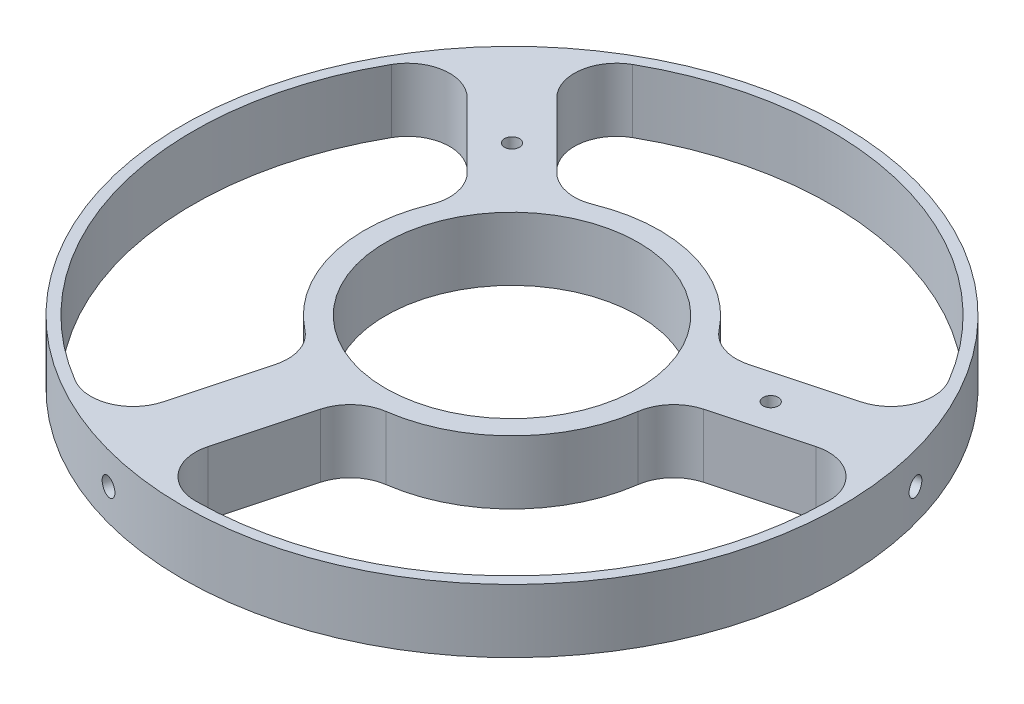
SolidWorks part; units mm, degrees
material "6061-T6 (SS)"
ref_plane "Front Plane" through (0, 0, 0) normal (0, 0, 1) x (1, 0, 0)
ref_plane "Top Plane" through (0, 0, 0) normal (0, 1, 0) x (1, 0, 0)
ref_plane "Right Plane" through (0, 0, 0) normal (1, 0, 0) x (0, 0, -1)
other "6062"
other "6061"
sketch "Sketch2" plane through (0, 0, 0) normal (0, 1, 0) x (1, 0, 0)
  circle A0 centre (0, 0) radius 49.53
  dimension "D1" = 99.06
extrude "Boss-Extrude1" add sketch "Sketch2" along normal blind 9.525
sketch "Sketch3" plane through (0, 9.525, 0) normal (0, 1, 0) x (1, 0, 0)
  circle A0 centre (0, 0) radius 19
  dimension "D1" = 38
extrude "Cut-Extrude1" cut sketch "Sketch3" against normal up to next
sketch "Sketch4" plane through (0, 9.525, 0) normal (0, 1, 0) x (1, 0, 0)
  line L0 (0, 0) -> (0, -34.925) construction
  line L1 (0, -34.925) -> (-6.35, -34.925) construction
  line L3 (-6.35, -34.925) -> (6.35, -34.925)
  line L4 (-6.35, -34.925) -> (-6.35, -60.325)
  line L5 (-6.35, -60.325) -> (6.35, -60.325)
  line L6 (6.35, -34.925) -> (6.35, -60.325)
  dimension "D1" = 34.925
  dimension "D2" = 6.35
  dimension "D3" = 12.7
  dimension "D4" = 25.4
extrude "Cut-Extrude2" [suppressed] cut sketch "Sketch4" against normal up to next
fillet "Fillet1" [suppressed] radius 3.175
ref_plane "Plane1" through (0, 0, 0) normal (0.7071, 0, -0.7071) x (-0.7071, 0, -0.7071)
hole_wizard "Tap Drill for #6-32 Tap1" positions "3DSketch4" profile "Sketch7" hole size "#6-32" standard "ANSI Inch"
sketch3d "3DSketch4"
  point P0 (-35.023, 4.7625, -35.023)
  dimension "D1" = 4.7625
sketch "Sketch7" plane through (-35.023, 4.7625, -35.023) normal (0, 1, 0) x (-0.7071, 0, 0.7071)
  line L0 (0, 0) -> (0, 14.7827)
  line L1 (0, 14.7827) -> (1.3525, 13.97)
  line L2 (1.3525, 13.97) -> (1.3525, 0)
  line L5 (1.3525, 0) -> (0, 0)
  line L10 (0, 14.7827) -> (-1.3526, 13.97) construction
  line L11 (0, -9.144) -> (0, 105.156) construction
  dimension "Hole Dia." = 2.7051
  dimension "Hole Depth" = 13.97
  dimension "Drill Angle" = 118
pattern_circular "CirPattern1" count 3 every 120 about axis through (0, -0.001, 0) along (0, 1, 0) of "Tap Drill for #6-32 Tap1"
sketch "Sketch8" plane through (0, 9.525, 0) normal (0, 1, 0) x (1, 0, 0)
  line L0 (0, 0) -> (-59.925, 0) construction
  line L3 (0, 0) -> (-52.2064, 52.2064) construction
  line L4 (0, 0) -> (64.6708, 17.3285) construction
  line L8 (-30.3652, 37.1004) -> (-11.9466, 18.6818)
  line L9 (44.8472, 16.9473) -> (19.687, 10.2056)
  circle A2 centre (0, 0) radius 19 construction
  circle A3 centre (0, 0) radius 49.53 construction
  arc A4 (-11.9466, 18.6818) -> (19.687, 10.2056) centre (0, 0) cw
  arc A5 (-30.3652, 37.1004) -> (44.8472, 16.9473) centre (0, 0) cw
  point P26 (0, -2.3141)
  dimension "D1" = 120
  dimension "D2" = 4.7625
  dimension "D4" = 3.175
  dimension "D5" = 1.5875
  dimension "D6" = 45
  dimension "D3" = 4.7625
extrude "Cut-Extrude3" cut sketch "Sketch8" against normal up to next
fillet "Fillet2" radius 6.35 4 edges at (-30.3652, 4.7625, -37.1004) (-11.9466, 4.7625, -18.6818) (19.687, 4.7625, -10.2056) (44.8472, 4.7625, -16.9473)
pattern_circular "CirPattern2" count 3 every 120 about axis through (0, 0, 0) along (0, 1, 0) of "Fillet2", "Cut-Extrude3"
sketch "Sketch9" plane through (0, 0, 0) normal (0, -1, 0) x (-1, 0, 0)
  circle A0 centre (0, 0) radius 22
  dimension "D1" = 44
split line "Split Line1"
sketch "Sketch11" plane through (0, 9.525, 0) normal (0, 1, 0) x (1, 0, 0)
  line L0 (0, 0) -> (-22.4506, 22.4506) construction
  line L1 (0, 0) -> (30.6681, 8.2175) construction
  line L2 (39.9474, 5.7734) -> (26.6089, 2.1993) construction
  line L3 (-21.9443, 15.2091) -> (-31.7088, 24.9736) construction
  circle A0 centre (0, 0) radius 31.75 construction
  point P4 (-22.4506, 22.4506)
  point P5 (30.6681, 8.2175)
  dimension "D1" = 63.5
hole_wizard "#4-40 Tapped Hole1" positions "Sketch11" profile "Sketch12" tap size "#4-40" standard "ANSI Inch" end condition through all
cosmetic thread "Hole Thread1" parameters "D2"=2.8448
cosmetic thread "Hole Thread2" parameters "D2"=2.8448
sketch "Sketch12" plane through (30.6681, 9.525, -8.2175) normal (1, 0, 0) x (0, 0, 1)
  line L0 (0, 0) -> (0, 9.525)
  line L1 (0, 9.525) -> (1.1303, 9.525)
  line L2 (1.1303, 9.525) -> (1.1303, 0)
  line L5 (1.1303, 0) -> (0, 0)
  line L11 (0, -6.35) -> (0, 107.95) construction
  dimension "Thru Tap Drill Dia." = 2.2606
  dimension "Thru Tap Drill Depth" = 9.525
